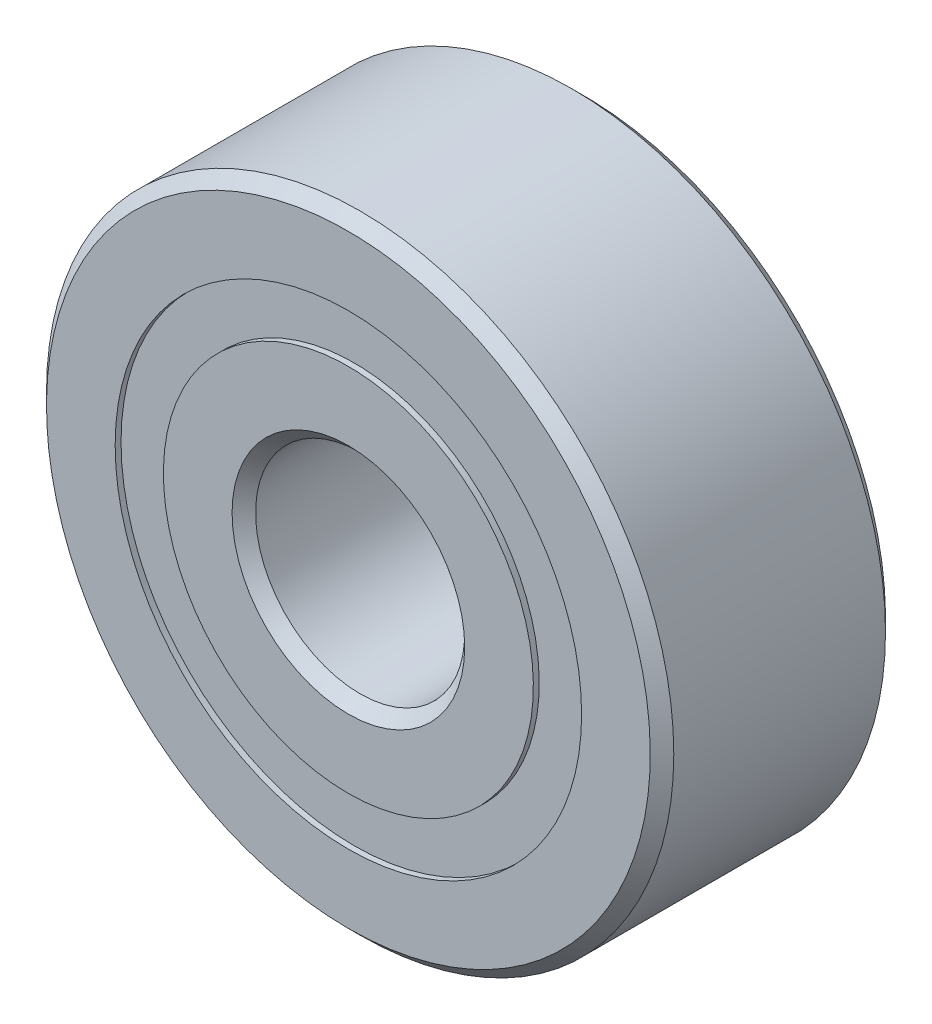
SolidWorks part; units mm, degrees
ref_plane "Front Plane" through (0, 0, 0) normal (0, 0, 1) x (1, 0, 0)
ref_plane "Top Plane" through (0, 0, 0) normal (0, 1, 0) x (1, 0, 0)
ref_plane "Right Plane" through (0, 0, 0) normal (1, 0, 0) x (0, 0, -1)
sketch "Sketch1" plane through (0, 0, 0) normal (0, 0, 1) x (1, 0, 0)
  line L0 (-9.525, 0) -> (9.525, 0) construction
  line L1 (-3.175, 0) -> (3.175, 0) construction
  circle A0 centre (0, 0) radius 3.175 construction
  circle A1 centre (0, 0) radius 9.525 construction
  point P3 (0, 0)
  point P6 (0, 0)
  point P7 (0, -3.175)
  point P11 (0, -9.525)
  point P12 (0, 3.175)
  point P13 (0, 9.525)
  dimension "OD" = 19.05
  dimension "ID" = 6.35
sketch "SketchB" plane through (0, 0, 0) normal (1, 0, 0) x (0, 0, -1)
  line L0 (-3.5719, 9.525) -> (3.5719, 9.525) construction
  line L1 (0, 9.525) -> (0, -9.525) construction
  line L2 (3.2147, 9.525) -> (-3.2147, 9.525)
  line L3 (-3.2147, 9.525) -> (-3.5719, 9.1678)
  line L4 (-3.5719, 9.1678) -> (-3.5719, 7.0827)
  line L5 (-3.5719, 7.0827) -> (-1.5875, 7.0827)
  line L6 (3.5719, 7.0827) -> (1.5875, 7.0827)
  line L7 (3.5719, 9.1678) -> (3.5719, 7.0827)
  line L8 (3.2147, 9.525) -> (3.5719, 9.1678)
  line L9 (0, 9.525) -> (0, 6.35) construction
  line L10 (0, 6.35) -> (0, 3.175) construction
  line L11 (0, 9.525) -> (0, -9.525) construction
  line L12 (-3.5719, 0) -> (3.5719, 0) construction
  line L13 (3.5719, 3.175) -> (-3.5719, 3.175) construction
  line L15 (-3.5719, -3.175) -> (3.5719, -3.175) construction
  arc A0 (-1.5875, 7.0827) -> (1.5875, 7.0827) centre (0, 6.35) cw
  circle A1 centre (0, 6.35) radius 1.7484 construction
  point P14 (0, 3.175)
  point P17 (0, 0)
  point P21 (0, 9.525)
  point P29 (0, 3.175)
  point P30 (0, -3.175)
  dimension "Width" = 7.1437
  dimension "D1" = 45
  dimension "D2" = 0.3572
  dimension "D3" = 3.175
  dimension "D4" = 0.7327
sketch "Sketch7" plane through (0, 0, 0) normal (1, 0, 0) x (0, 0, -1)
  line L0 (3.2147, 9.525) -> (3.5719, 9.1678) construction
  line L1 (3.5719, 9.1678) -> (3.5719, 7.0827) construction
  line L2 (3.5719, 7.0827) -> (1.5875, 7.0827) construction
  line L3 (-3.5719, 7.0827) -> (-1.5875, 7.0827) construction
  line L4 (-3.5719, 9.1678) -> (-3.5719, 7.0827) construction
  line L5 (-3.2147, 9.525) -> (-3.5719, 9.1678) construction
  line L6 (3.2147, 9.525) -> (-3.2147, 9.525) construction
  line L7 (3.2147, 9.525) -> (3.5719, 9.1678)
  line L8 (3.5719, 9.1678) -> (3.5719, 7.0827)
  line L9 (3.5719, 7.0827) -> (1.5875, 7.0827)
  line L10 (-3.5719, 7.0827) -> (-1.5875, 7.0827)
  line L11 (-3.5719, 9.1678) -> (-3.5719, 7.0827)
  line L12 (-3.2147, 9.525) -> (-3.5719, 9.1678)
  line L13 (3.2147, 9.525) -> (-3.2147, 9.525)
  arc A0 (1.5875, 7.0827) -> (-1.5875, 7.0827) centre (0, 6.35) ccw construction
  arc A1 (1.5875, 7.0827) -> (-1.5875, 7.0827) centre (0, 6.35) ccw
revolve "Revolve6" add sketch "Sketch7" angle 360 about L12
sketch "Sketch3" plane through (0, 0, 0) normal (1, 0, 0) x (0, 0, -1)
  line L0 (0, 9.525) -> (0, -9.525) construction
  line L1 (0, 9.525) -> (0, -9.525) construction
  line L2 (-3.2147, 3.175) -> (-3.5719, 3.5322)
  line L3 (-3.5719, 3.5322) -> (-3.5719, 5.6173)
  line L5 (-3.5719, 5.6173) -> (-1.5875, 5.6173)
  line L6 (-3.2147, 3.175) -> (3.2147, 3.175)
  line L8 (3.2147, 3.175) -> (3.5719, 3.5322)
  line L10 (3.5719, 3.5322) -> (3.5719, 5.6173)
  line L11 (3.5719, 5.6173) -> (1.5875, 5.6173)
  line L12 (-3.5719, 9.1678) -> (-3.5719, 7.0827) construction
  line L13 (3.2147, 9.525) -> (3.5719, 9.1678) construction
  line L15 (3.5719, -9.1678) -> (3.5719, 9.1678) construction
  line L16 (3.2147, 9.525) -> (3.2147, -9.525) construction
  arc A1 (1.5875, 5.6173) -> (-1.5875, 5.6173) centre (0, 6.35) cw
  circle A2 centre (0, 6.35) radius 1.7484 construction
  point P1 (0, 3.175)
revolve "Revolve3" add sketch "Sketch3" angle 360 about L12
sketch "Sketch4" plane through (0, 0, 0) normal (1, 0, 0) x (0, 0, -1)
  line L0 (-1.7484, 6.35) -> (1.7484, 6.35)
  arc A2 (-1.7484, 6.35) -> (1.7484, 6.35) centre (0, 6.35) cw
  arc A3 (1.5875, 7.0827) -> (-1.5875, 7.0827) centre (0, 6.35) ccw construction
revolve "Revolve4" add sketch "Sketch4" angle 360 about L0
pattern_circular "CirPattern1" count 8 over 360 about axis through (0, 0, 0) along (0, 0, 1) of bodies 104
sketch "Sketch5" plane through (0, 0, 0) normal (1, 0, 0) x (0, 0, -1)
  line L0 (-3.5719, 7.0827) -> (-1.5875, 7.0827) construction
  line L1 (-3.3933, 7.0827) -> (-1.7484, 7.0827)
  line L2 (-3.3933, 7.0827) -> (-3.3933, 5.6173)
  line L3 (-3.3933, 5.6173) -> (-1.7484, 5.6173)
  line L4 (-1.7484, 7.0827) -> (-1.7484, 5.6173)
  line L5 (-3.5719, 5.6173) -> (-1.5875, 5.6173) construction
  line L6 (-3.2147, 9.525) -> (-3.5719, 9.1678) construction
  line L7 (0, 9.525) -> (0, 3.175) construction
  line L8 (3.3933, 5.6173) -> (1.7484, 5.6173)
  line L9 (1.7484, 7.0827) -> (1.7484, 5.6173)
  line L10 (3.3933, 7.0827) -> (1.7484, 7.0827)
  line L11 (3.3933, 7.0827) -> (3.3933, 5.6173)
  circle A1 centre (0, 6.35) radius 1.7484 construction
  point P10 (-3.3933, 9.3464)
revolve "Revolve5" add sketch "Sketch5" angle 360 about L12
equation "\"D2@SketchB\" = \"Width@SketchB\" * .05"
equation "\"D3@SketchB\" = \"Width@SketchB\" / 2.25"
equation "\"D4@SketchB\" =  (  (  ( \"OD@Sketch1\" - \"Width@SketchB\" )  / 2 )  / 3.25 )  / 2.5"
